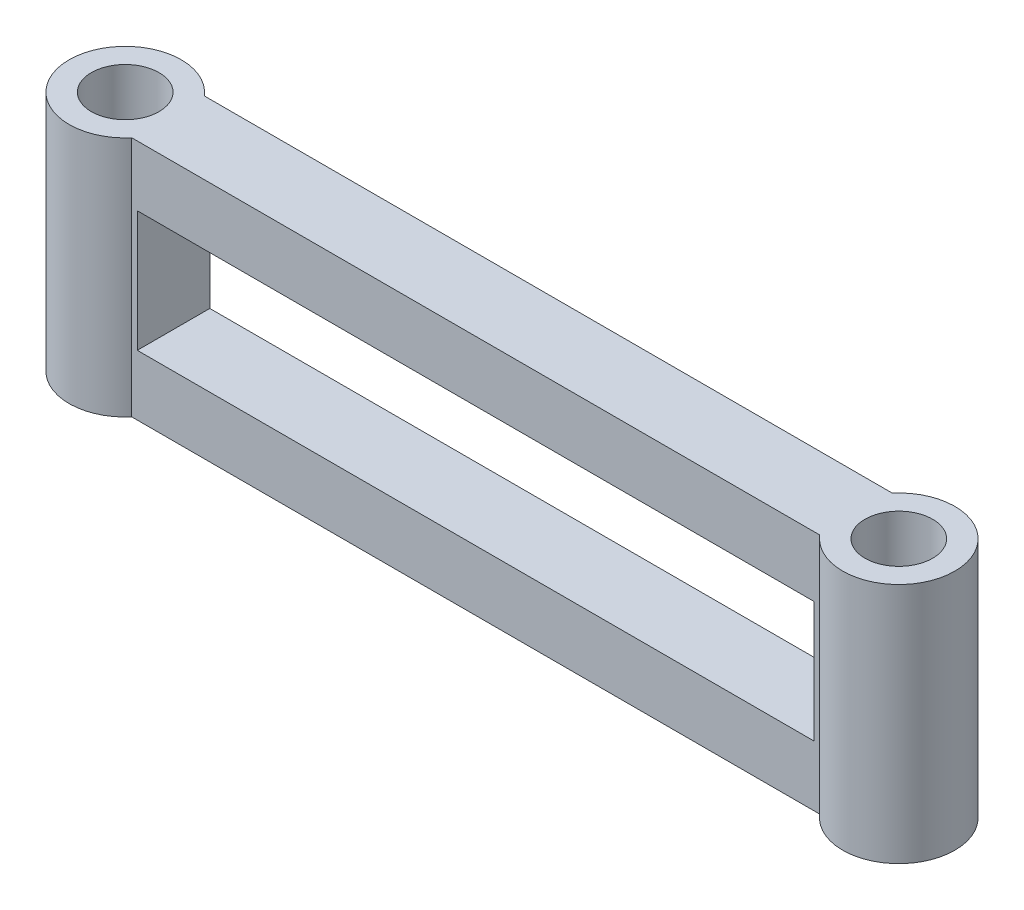
SolidWorks part; units mm, degrees
ref_plane "Front Plane" through (0, 0, 0) normal (0, 0, 1) x (1, 0, 0)
ref_plane "Top Plane" through (0, 0, 0) normal (0, 1, 0) x (1, 0, 0)
ref_plane "Right Plane" through (0, 0, 0) normal (1, 0, 0) x (0, 0, -1)
sketch "Sketch1" plane through (0, 0, 0) normal (0, 1, 0) x (1, 0, 0)
  line L0 (-101.6, 49.5042) -> (-90.3614, 59.0292) construction
  line L5 (-101.6, 49.5042) -> (-90.3614, 39.9792) construction
  line L6 (101.6, 49.5042) -> (90.3614, 59.0292) construction
  line L7 (101.6, 49.5042) -> (90.3614, 39.9792) construction
  line L8 (-90.3614, 59.0292) -> (90.3614, 59.0292)
  line L9 (-90.3614, 39.9792) -> (90.3614, 39.9792)
  circle A1 centre (101.6, 49.5042) radius 8.89
  circle A2 centre (-101.6, 49.5042) radius 8.89
  arc A3 (-90.3614, 59.0292) -> (-90.3614, 39.9792) centre (-101.6, 49.5042) ccw
  arc A4 (90.3614, 39.9792) -> (90.3614, 59.0292) centre (101.6, 49.5042) ccw
  point P0 (116.332, 49.5042)
  point P1 (-116.332, 49.5042)
  point P2 (0, 0)
  point P8 (0, 0)
  point P12 (0, 0)
  point P13 (0, 0)
  dimension "D1" = 203.2
  dimension "D3" = 19.05
  dimension "D2" = 14.732
  dimension "D4" = 19.05
  dimension "D5" = 14.732
  dimension "D6" = 0
  dimension "D7" = 0
  dimension "D8" = 101.6
extrude "Boss-Extrude1" add sketch "Sketch1" along normal blind 63.5
sketch "Sketch2" plane through (0, 0, -39.9792) normal (0, 0, 1) x (1, 0, 0)
  line L1 (-88.9, 47.625) -> (88.9, 47.625)
  line L2 (-88.9, 47.625) -> (-88.9, 15.875)
  line L3 (-88.9, 15.875) -> (88.9, 15.875)
  line L4 (88.9, 47.625) -> (88.9, 15.875)
  dimension "D1" = 31.75
  dimension "D2" = 177.8
  dimension "D3" = 88.9
  dimension "D4" = 15.875
extrude "Cut-Extrude1" cut sketch "Sketch2" against normal through all
